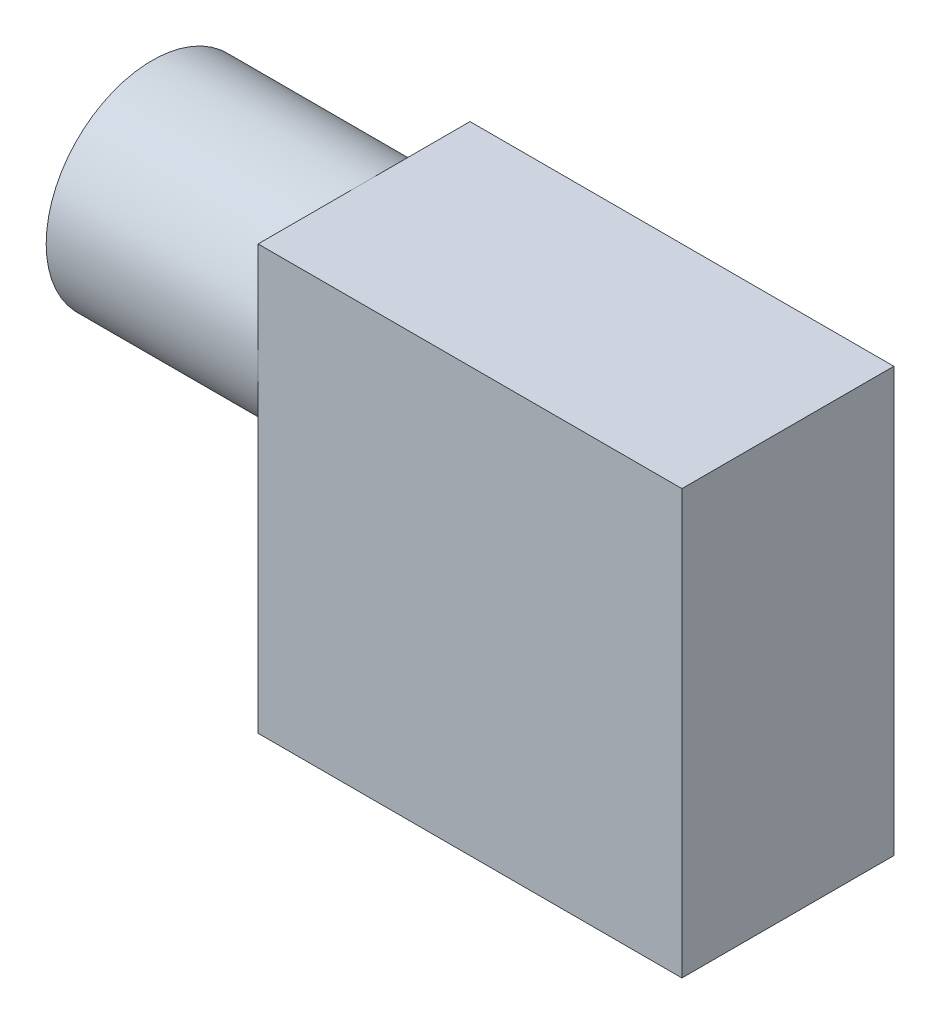
SolidWorks part; units mm, degrees
material "3d打印 35%"
ref_plane "前视基准面" through (0, 0, 0) normal (0, 0, 1) x (1, 0, 0)
ref_plane "上视基准面" through (0, 0, 0) normal (0, 1, 0) x (1, 0, 0)
ref_plane "右视基准面" through (0, 0, 0) normal (1, 0, 0) x (0, 0, -1)
other "Configuration Table"
sketch "草图1" plane through (0, 0, 0) normal (0, 0, 1) x (1, 0, 0)
  line L0 (0, 0) -> (20, 0)
  line L1 (20, 0) -> (20, -20)
  line L2 (20, -20) -> (0, -20)
  line L3 (0, -20) -> (0, 0)
  dimension "D1" = 20
  dimension "D2" = 20
extrude "凸台-拉伸1" add sketch "草图1" along normal blind 10
sketch "草图2" plane through (0, 0, 0) normal (-1, 0, 0) x (0, 0, 1)
  line L0 (10, 0) -> (10, -20) construction
  line L1 (10, 0) -> (0, 0) construction
  circle A0 centre (5, -5) radius 5
  dimension "D1" = 10
extrude "凸台-拉伸2" add sketch "草图2" along normal blind 10
